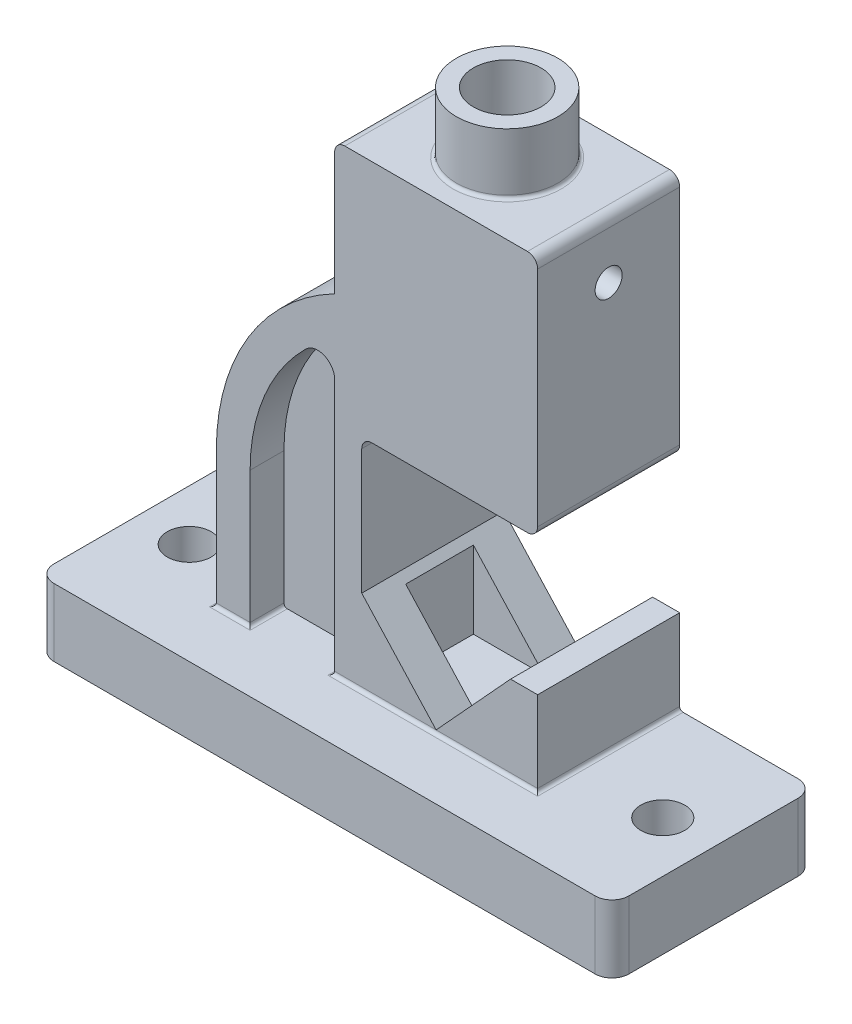
SolidWorks part; units mm, degrees
ref_plane "Front Plane" through (0, 0, 0) normal (0, 0, 1) x (1, 0, 0)
ref_plane "Top Plane" through (0, 0, 0) normal (0, 1, 0) x (1, 0, 0)
ref_plane "Right Plane" through (0, 0, 0) normal (1, 0, 0) x (0, 0, -1)
sketch "Sketch1" plane through (0, 0, 0) normal (0, 1, 0) x (1, 0, 0)
  line L0 (0, -55) -> (0, 55) construction
  line L1 (80, -30) -> (-80, -30)
  line L2 (85, -25) -> (85, 25)
  line L3 (80, 30) -> (-80, 30)
  line L4 (-85, -25) -> (-85, 25)
  line L5 (85, -30) -> (-85, 30) construction
  line L6 (85, 30) -> (-85, -30) construction
  circle A0 centre (-70, 0) radius 6.5
  circle A1 centre (70, 0) radius 6.5
  arc A2 (80, -30) -> (85, -25) centre (80, -25) ccw
  arc A3 (85, 25) -> (80, 30) centre (80, 25) ccw
  arc A4 (-80, -30) -> (-85, -25) centre (-80, -25) cw
  arc A5 (-80, 30) -> (-85, 25) centre (-80, 25) ccw
  point P0 (0, 0)
  point P9 (-85, 0)
  dimension "D3" = 13
  dimension "D4" = 140
  dimension "D5" = 5
  dimension "D1" = 170
  dimension "D2" = 60
extrude "Boss-Extrude1" add sketch "Sketch1" along normal blind 20
ref_plane "Plane1" through (0, 0, 12) normal (0, 0, 1) x (1, 0, 0)
sketch "Sketch2" plane through (0, 0, 12) normal (0, 0, 1) x (1, 0, 0)
  line L0 (15, 20.9912) -> (15, 40.9474) construction
  line L1 (-80, 20) -> (80, 20) construction
  line L2 (15, 20.9912) -> (-7, 45)
  line L3 (-7, 45) -> (-7, 85)
  line L4 (45, 85) -> (45, 157)
  line L5 (45, 157) -> (-15, 157)
  line L6 (-15, 157) -> (-15, 117.6628)
  line L7 (-50, 60) -> (-50, 20)
  line L8 (-7, 85) -> (45, 85)
  line L10 (15, 20.9912) -> (37, 45)
  line L11 (85, 20) -> (85, 0) construction
  line L12 (37, 45) -> (45, 45)
  line L13 (45, 45) -> (45, 20)
  line L14 (45, 20) -> (-15, 20)
  line L15 (-15, 20) -> (-15, 95.7071)
  line L17 (-7, 85) -> (-15, 85) construction
  line L18 (-80, 0) -> (80, 0) construction
  line L19 (-40, 60) -> (-40, 20)
  line L20 (-40, 20) -> (-50, 20)
  arc A0 (-15, 117.6628) -> (-50, 60) centre (15, 60) ccw
  arc A1 (-15, 95.7071) -> (-23.5, 99.2779) centre (-20, 95.7071) ccw
  arc A2 (-23.5, 99.2779) -> (-40, 60) centre (15, 60) ccw
  dimension "D8" = 65
  dimension "D9" = 5
  dimension "D10" = 55
  dimension "D1" = 44
  dimension "D2" = 85
  dimension "D3" = 70
  dimension "D4" = 40
  dimension "D5" = 60
  dimension "D6" = 72
  dimension "D7" = 60
  dimension "D11" = 25
extrude "Boss-Extrude2" add sketch "Sketch2" against normal up to surface (42 mm away) contours A2 A1 L15 L14 L2 L3 L8 L4 L5 L6 A0 L7 L20 L19 | L14 L13 L12 L10 up to face at (0, 10, -30)
ref_plane "Plane2" through (0, 0, -9) normal (0, 0, 1) x (1, 0, 0)
sketch "Sketch4" plane through (0, 45, 0) normal (0, 1, 0) x (1, 0, 0)
  line L0 (15, 30) -> (15, -12) construction
  line L1 (35, -1) -> (-5, -1)
  line L2 (35, -1) -> (35, 19)
  line L3 (35, 19) -> (-5, 19)
  line L4 (-5, -1) -> (-5, 19)
  line L5 (35, -1) -> (-5, 19) construction
  line L6 (35, 19) -> (-5, -1) construction
  point P0 (15, 9)
  point P12 (-5, 9)
  point P15 (15, 9)
  dimension "D1" = 20
  dimension "D2" = 40
extrude "Cut-Extrude1" cut sketch "Sketch4" against normal up to surface (25 mm away) up to face at (-70, 20, 6.5)
sketch "Sketch5" plane through (0, 0, -9) normal (0, 0, 1) x (1, 0, 0)
  line L0 (-15, 20) -> (-15, 95.7071) construction
  line L1 (-40, 60) -> (-40, 20) construction
  line L2 (-15, 20) -> (-15, 95.7071)
  line L3 (-40, 60) -> (-40, 20)
  line L4 (-40, 20) -> (-15, 20)
  arc A0 (-15, 95.7071) -> (-23.5, 99.2779) centre (-20, 95.7071) ccw construction
  arc A1 (-23.5, 99.2779) -> (-40, 60) centre (15, 60) ccw construction
  arc A2 (-15, 95.7071) -> (-23.5, 99.2779) centre (-20, 95.7071) ccw
  arc A3 (-23.5, 99.2779) -> (-40, 60) centre (15, 60) ccw
extrude "Boss-Extrude3" add sketch "Sketch5" along normal mid plane 22
fillet "Fillet1" radius 3 4 edges at (-7, 85, -9) (45, 85, -9) (-15, 157, -9) (45, 157, -9)
sketch "Sketch7" plane through (0, 157, 0) normal (0, 1, 0) x (1, 0, 0)
  line L1 (42, -12) -> (42, 30) construction
  circle A0 centre (15, 9) radius 10
  circle A1 centre (15, 9) radius 15
  point P7 (42, 9)
  dimension "D1" = 30
  dimension "D2" = 20
extrude "Boss-Extrude4" add sketch "Sketch7" along normal blind 18
fillet "Fillet2" radius 1 7 edges at (15, 20, 12) (45, 20, -9) (-15, 20, 7) (-40, 20, 7) (-50, 20, -9) (-45, 20, 12) (15, 157, 6)
sketch "Sketch8" plane through (0, 157, 0) normal (0, 1, 0) x (1, 0, 0)
  circle A1 centre (15, 9) radius 10
  circle A2 centre (15, 9) radius 10
  dimension "D1" = 0
extrude "Cut-Extrude2" cut sketch "Sketch8" against normal blind 94
sketch "Sketch9" plane through (0, 0, -9) normal (1, 0, 0) x (0, 0, -1)
  line L3 (-21, 157) -> (21, 157) construction
  line L4 (15, 158) -> (15, 175) construction
  circle A0 centre (0, 140) radius 4
  point P2 (10, 142.0674)
  point P3 (2.0127, 142.3066)
  point P4 (0, 0)
  dimension "D1" = 8
  dimension "D2" = 17
  dimension "D3" = 15
extrude "Cut-Extrude3" cut sketch "Sketch9" along normal through all both and the other way through all
